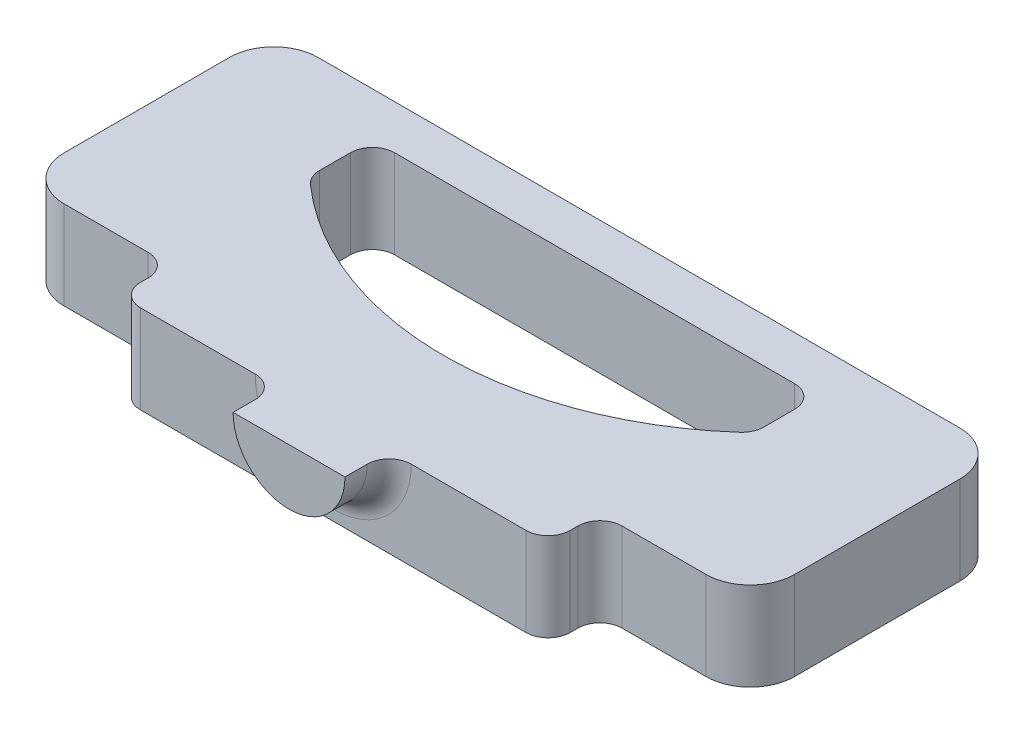
SolidWorks part; units mm, degrees
ref_plane "Front Plane" through (0, 0, 0) normal (0, 0, 1) x (1, 0, 0)
ref_plane "Top Plane" through (0, 0, 0) normal (0, 1, 0) x (1, 0, 0)
ref_plane "Right Plane" through (0, 0, 0) normal (1, 0, 0) x (0, 0, -1)
sketch "Sketch1" plane through (0, 0, 0) normal (0, 1, 0) x (1, 0, 0)
  line L0 (0, 30.0765) -> (0, 6.35)
  line L1 (6.35, 0) -> (18.4019, 0)
  line L2 (21.5769, -3.175) -> (21.5769, -4.2698)
  line L3 (24.7519, -7.4448) -> (80.0876, -7.4448)
  line L4 (52.4197, -7.4448) -> (52.4197, 53.975) construction
  line L5 (83.2626, -3.175) -> (83.2626, -4.2698)
  line L6 (98.4894, 0) -> (86.4376, 0)
  line L7 (104.8394, 30.0765) -> (104.8394, 6.35)
  line L8 (6.35, 36.4265) -> (98.4894, 36.4265)
  line L9 (81.1361, 30.0765) -> (23.7033, 30.0765)
  line L10 (84.3111, 26.9015) -> (84.3111, 22.477)
  line L11 (20.5283, 26.9015) -> (20.5283, 22.477)
  arc A0 (6.35, 36.4265) -> (0, 30.0765) centre (6.35, 30.0765) ccw
  arc A1 (104.8394, 30.0765) -> (98.4894, 36.4265) centre (98.4894, 30.0765) ccw
  arc A2 (6.35, 0) -> (0, 6.35) centre (6.35, 6.35) cw
  arc A3 (104.8394, 6.35) -> (98.4894, 0) centre (98.4894, 6.35) cw
  arc A4 (21.5769, -3.175) -> (18.4019, 0) centre (18.4019, -3.175) ccw
  arc A5 (83.2626, -3.175) -> (86.4376, 0) centre (86.4376, -3.175) cw
  arc A6 (24.7519, -7.4448) -> (21.5769, -4.2698) centre (24.7519, -4.2698) cw
  arc A7 (83.2626, -4.2698) -> (80.0876, -7.4448) centre (80.0876, -4.2698) cw
  arc A8 (21.5943, 20.1036) -> (83.2452, 20.1036) centre (52.4197, 54.7924) ccw
  arc A9 (23.7033, 30.0765) -> (20.5283, 26.9015) centre (23.7033, 26.9015) ccw
  arc A10 (84.3111, 26.9015) -> (81.1361, 30.0765) centre (81.1361, 26.9015) ccw
  arc A11 (84.3111, 22.477) -> (83.2452, 20.1036) centre (81.1361, 22.477) cw
  arc A12 (20.5283, 22.477) -> (21.5943, 20.1036) centre (23.7033, 22.477) ccw
  point P13 (0, 36.4265)
  point P16 (104.8394, 36.4265)
  point P19 (0, 0)
  point P22 (104.8394, 0)
  point P25 (21.5769, 0)
  point P28 (83.2626, 0)
  point P31 (21.5769, -7.4448)
  point P34 (83.2626, -7.4448)
  point P42 (20.5283, 30.0765)
  point P45 (84.3111, 30.0765)
  point P48 (84.3111, 21.0811)
  point P51 (20.5283, 21.0811)
extrude "Extrude1" add sketch "Sketch1" against normal blind 12.7
ref_plane "Plane1" through (0, 0, 7.4448) normal (0, 0, 1) x (1, 0, 0)
sketch "Sketch2" plane through (0, 0, 7.4448) normal (0, 0, 1) x (1, 0, 0)
  line L0 (24.7519, 0) -> (80.0876, 0) construction
  line L1 (44.3899, 0) -> (60.4495, 0)
  arc A0 (44.3899, 0) -> (60.4495, 0) centre (52.4197, 0) ccw
extrude "Extrude2" add sketch "Sketch2" along normal blind 6.35
fillet "Fillet1" radius 3.175 1 edges at (52.4197, -8.0298, 7.4448)
